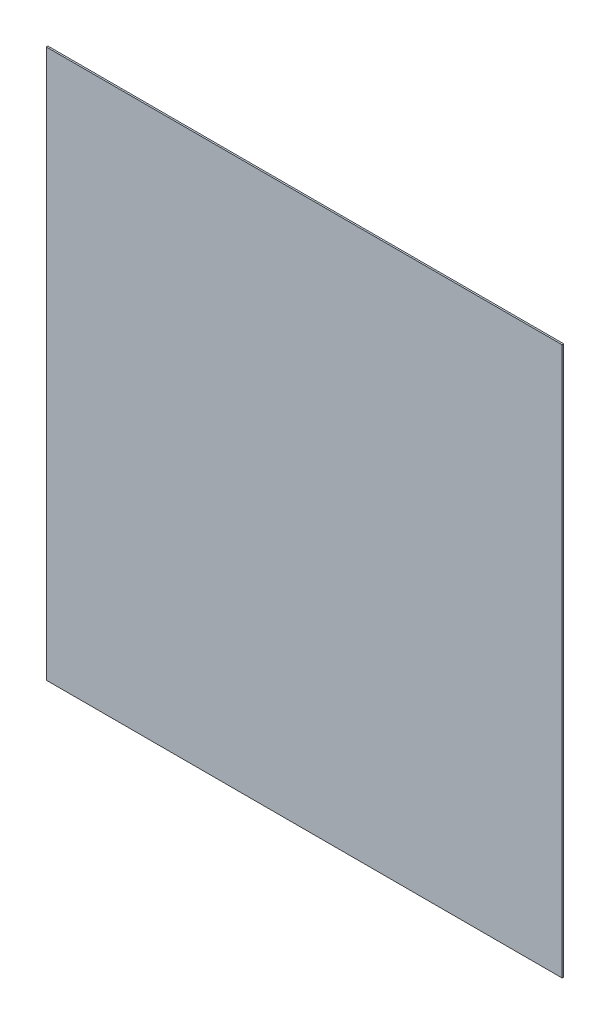
SolidWorks part; units mm, degrees
material "Akryl (Średnie-wysokie uderzenie)"
ref_plane "Płaszczyzna przednia" through (0, 0, 0) normal (0, 0, 1) x (1, 0, 0)
ref_plane "Płaszczyzna górna" through (0, 0, 0) normal (0, 1, 0) x (1, 0, 0)
ref_plane "Płaszczyzna prawa" through (0, 0, 0) normal (1, 0, 0) x (0, 0, -1)
sketch "Szkic1" plane through (0, 0, 0) normal (0, 0, 1) x (1, 0, 0)
  line L1 (0, 0) -> (1580, 0)
  line L2 (0, 0) -> (0, 1680)
  line L3 (0, 1680) -> (1580, 1680)
  line L4 (1580, 0) -> (1580, 1680)
  dimension "D1" = 1680
  dimension "D2" = 1580
extrude "Dodanie-wyciągnięcie1" add sketch "Szkic1" along normal blind 5 contours L2 L3 L4 L1
